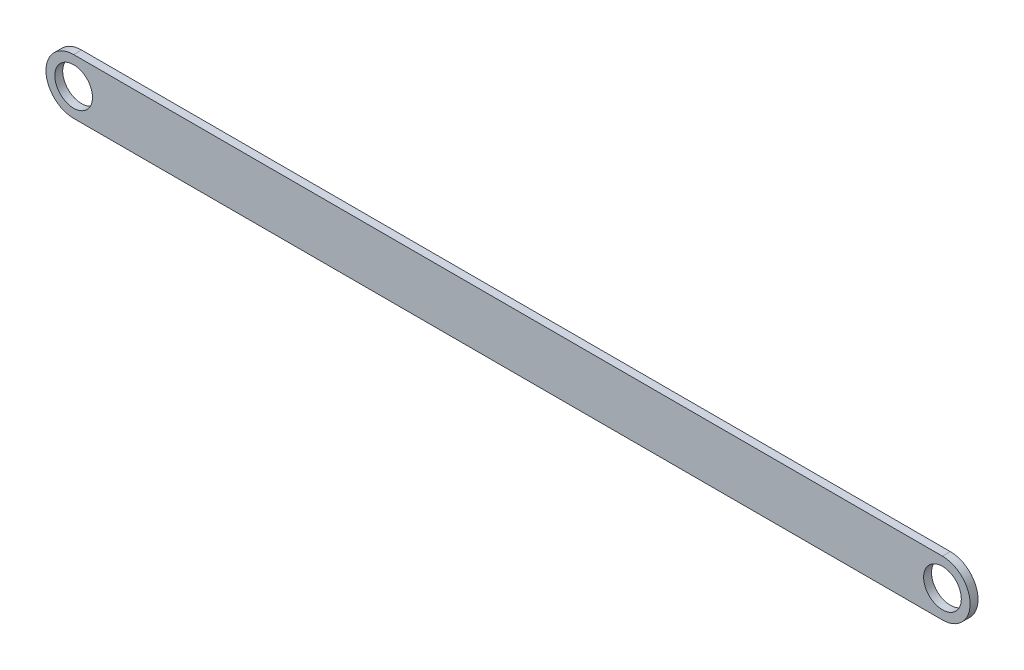
SolidWorks part; units mm, degrees
ref_plane "前视基准面" through (0, 0, 0) normal (0, 0, 1) x (1, 0, 0)
ref_plane "上视基准面" through (0, 0, 0) normal (0, 1, 0) x (1, 0, 0)
ref_plane "右视基准面" through (0, 0, 0) normal (1, 0, 0) x (0, 0, -1)
sketch "草图1" plane through (0, 0, 0) normal (0, 0, 1) x (1, 0, 0)
  line L28 (0, 0) -> (440, 0) construction
  line L29 (0, 14) -> (440, 14)
  line L30 (440, -14) -> (0, -14)
  circle A24 centre (0, 0) radius 14 construction
  circle A25 centre (0, 0) radius 9.54
  circle A26 centre (440, 0) radius 9.54
  circle A27 centre (440, 0) radius 14 construction
  arc A28 (0, 14) -> (0, -14) centre (0, 0) ccw
  arc A29 (440, 14) -> (440, -14) centre (440, 0) cw
  dimension "D1" = 19.08
  dimension "D2" = 28
extrude "凸台-拉伸1" add sketch "草图1" along normal blind 4
